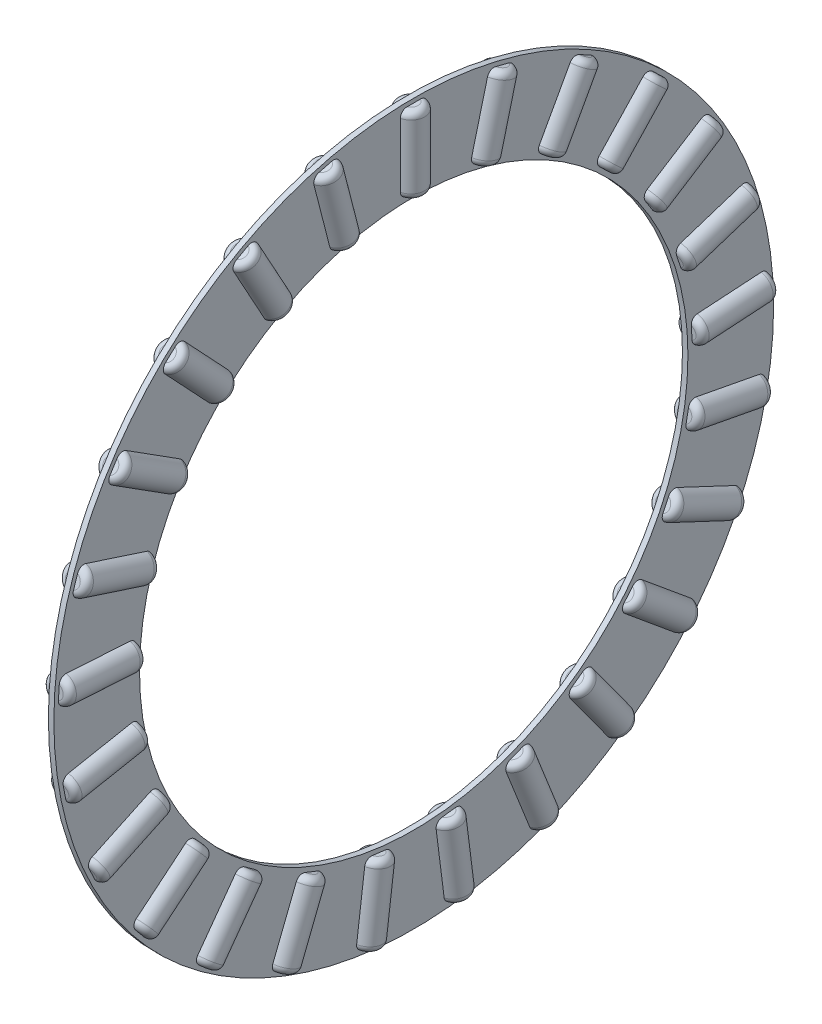
SolidWorks part; units mm, degrees
ref_plane "Plane1" through (0, 0, 0) normal (0, 0, 1) x (1, 0, 0)
ref_plane "Plane2" through (0, 0, 0) normal (0, 1, 0) x (1, 0, 0)
ref_plane "Plane3" through (0, 0, 0) normal (1, 0, 0) x (0, 0, -1)
sketch "Clipboard" plane through (0, 0, 0) normal (0, 0, 1) x (1, 0, 0)
  line L0 (-10, 0) -> (10, 0) construction
  line L1 (0, 0) -> (20.2657, -9.45)
  line L2 (0, 0) -> (41.9167, 19.5461)
  line L3 (0, 0) -> (20.2657, -9.45)
  line L4 (0, 0) -> (-22.3471, -0.7804)
  dimension "BallCLRad" = 46.25
  dimension "Count" = 25
  dimension "Show_count" = 25
  dimension "Max_count" = 25
  dimension "Min_count" = 2
sketch "CagSpiSke" plane through (0, 0, 0) normal (0, 0, 1) x (1, 0, 0)
  line L5 (-34.925, 0) -> (34.925, 0) construction
  line L6 (-0.4, 52.5) -> (0.4, 52.5)
  line L7 (-0.4, 52.5) -> (-0.4, 40)
  line L8 (-0.4, 40) -> (0.4, 40)
  line L9 (0.4, 52.5) -> (0.4, 40)
  dimension "ID" = 80
  dimension "OD" = 105
  dimension "Thickness" = 0.8
  dimension "HalfThick" = 0.4
revolve "CageSpine" add sketch "CagSpiSke" angle 360 about L5
ref_axis "Axis1" through (-50, 0, 0) along (1, 0, 0)
sketch "RolDetSke" plane through (0, 0, 0) normal (0, 0, 1) x (1, 0, 0)
  line L0 (0, 33.02) -> (0, 55.88) construction
  line L3 (0, 51.875) -> (1.04, 51.875)
  line L4 (0, 51.875) -> (0, 40.625)
  line L5 (0, 40.625) -> (1.04, 40.625)
  line L6 (2, 50.915) -> (2, 41.585)
  arc A0 (2, 41.585) -> (1.04, 40.625) centre (1.04, 41.585) cw
  arc A1 (1.04, 51.875) -> (2, 50.915) centre (1.04, 50.915) cw
  dimension "Roller_diameter" = 4
  dimension "Cyl_Len" = 11.25
  dimension "offset" = 40.625
  dimension "radius" = 0.96
revolve "RollerDetailed" add sketch "RolDetSke" angle 360 about L0
pattern_circular "RollersDetailed" count 25 every 14.4 about axis through (-50, 0, 0) along (1, 0, 0) of "RollerDetailed"
sketch "RolSimSke" plane through (0, 0, 0) normal (0, 0, 1) x (1, 0, 0)
  line L1 (-17.78, 0) -> (12.7, 0) construction
  line L3 (-1.04, 51.875) -> (1.04, 51.875)
  line L4 (-2, 50.915) -> (-2, 41.585)
  line L5 (-1.04, 40.625) -> (1.04, 40.625)
  line L6 (2, 50.915) -> (2, 41.585)
  arc A0 (-2, 41.585) -> (-1.04, 40.625) centre (-1.04, 41.585) ccw
  arc A1 (-1.04, 51.875) -> (-2, 50.915) centre (-1.04, 50.915) ccw
  arc A2 (2, 50.915) -> (1.04, 51.875) centre (1.04, 50.915) ccw
  arc A3 (1.04, 40.625) -> (2, 41.585) centre (1.04, 41.585) ccw
  dimension "Rol_rad" = 0.96
  dimension "Roller_diameter" = 4
  dimension "Cyl_Len" = 11.25
  dimension "Halfdia" = 2
  dimension "offset" = 40.625
revolve "RollersSimplified" [suppressed] add sketch "RolSimSke" angle 360 about L1
equation "\"BallCLRad@Clipboard\" =  ( \"OD@CagSpiSke\" + \"ID@CagSpiSke\" )  / 4"
equation "\"offset@RolSimSke\" = \"BallCLRad@Clipboard\" - \"Cyl_Len@RolSimSke\" / 2"
equation "\"offset@RolDetSke\" = \"BallCLRad@Clipboard\" - \"Cyl_Len@RolDetSke\" / 2"
equation "\"Thickness@CagSpiSke\" =  \"Roller_diameter@RolDetSke\" * 0.2"
equation "\"HalfThick@CagSpiSke\" = \"Thickness@CagSpiSke\" / 2"
equation "\"radius@RolDetSke\" =  ( \"Roller_diameter@RolDetSke\" - \"Thickness@CagSpiSke\" )  * 0.6 / 2"
equation "\"Roller_diameter@RolSimSke\" = \"Roller_diameter@RolDetSke\""
equation "\"Cyl_Len@RolSimSke\" = \"Cyl_Len@RolDetSke\""
equation "\"Rol_rad@RolSimSke\" = \"radius@RolDetSke\""
equation "\"Halfdia@RolSimSke\" = \"Roller_diameter@RolSimSke\" / 2"
equation "\"Max_count@Clipboard\" = int( 3.14159265 / atn(( \"Roller_diameter@RolDetSke\" / 2) / sqr( \"offset@RolDetSke\"  *  \"offset@RolDetSke\" - ( \"Roller_diameter@RolDetSke\" / 2) *  ( \"Roller_diameter@RolDetSke\" / 2))))"
equation "\"Max_count@Clipboard\" = ((sgn( \"Max_count@Clipboard\" - \"Count@Clipboard\" )-1)*( \"Max_count@Clipboard\" - \"Count@Clipboard\" ))/-2+ \"Count@Clipboard\""
equation "\"Count@RollersDetailed\" = int( \"Show_count@Clipboard\" ) "
equation "\"Count@RollersDetailed\" = ((sgn( \"Count@RollersDetailed\" - \"Max_count@Clipboard\" )-1)*( \"Count@RollersDetailed\" - \"Max_count@Clipboard\" ))/-2+ \"Max_count@Clipboard\""
equation "\"Count@RollersDetailed\" = ((sgn( \"Count@RollersDetailed\" - \"Min_count@Clipboard\" )+1)*( \"Count@RollersDetailed\" - \"Min_count@Clipboard\"))/2 +\"Min_count@Clipboard\""
equation "\"Angle@RollersDetailed\" = 360.0 / \"Max_count@Clipboard\""
